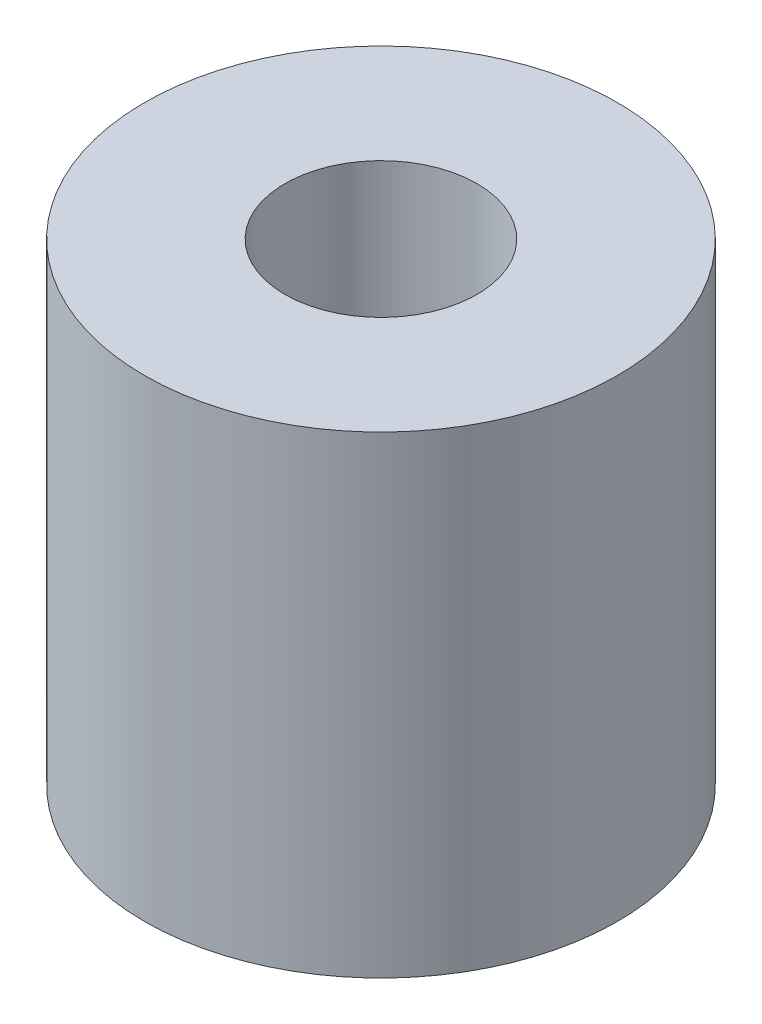
SolidWorks part; units mm, degrees
ref_plane "Front Plane" through (0, 0, 0) normal (0, 0, 1) x (1, 0, 0)
ref_plane "Top Plane" through (0, 0, 0) normal (0, 1, 0) x (1, 0, 0)
ref_plane "Right Plane" through (0, 0, 0) normal (1, 0, 0) x (0, 0, -1)
sketch "Sketch1" plane through (0, 0, 0) normal (0, 1, 0) x (1, 0, 0)
  circle A0 centre (0, 0) radius 2.5797
  circle A1 centre (0, 0) radius 6.35
  dimension "D1" = 5.1594
  dimension "D2" = 12.7
extrude "Boss-Extrude1" add sketch "Sketch1" along normal blind 12.7
